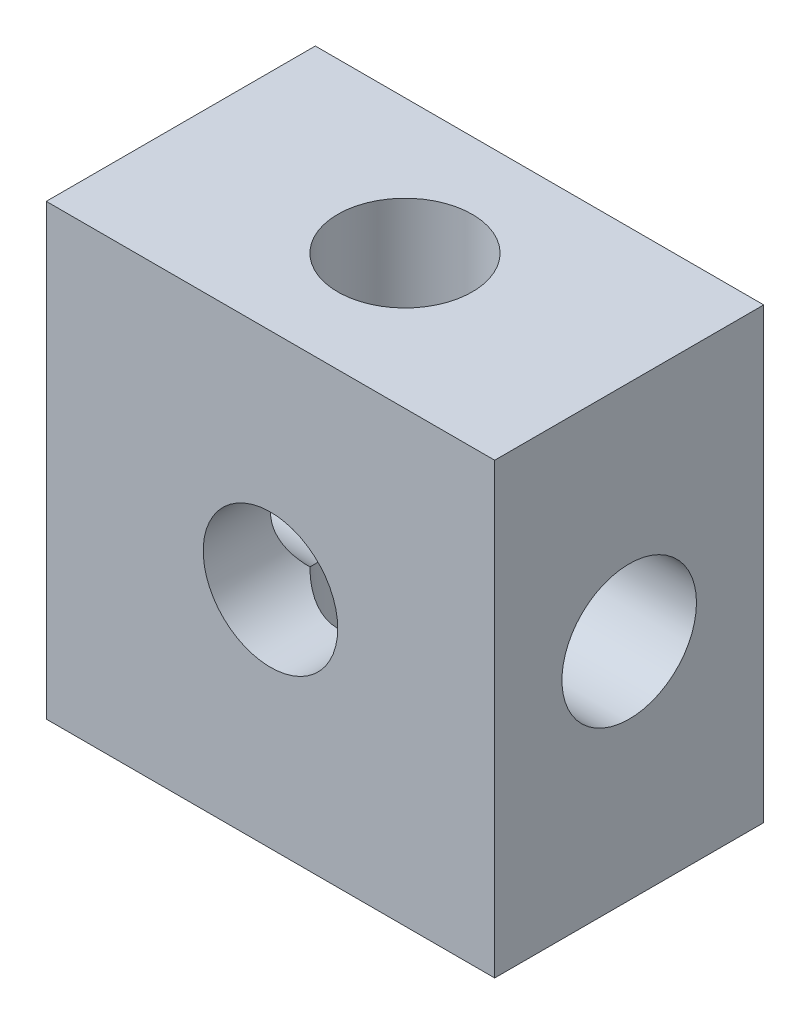
SolidWorks part; units mm, degrees
ref_plane "前视基准面" through (0, 0, 0) normal (0, 0, 1) x (1, 0, 0)
ref_plane "上视基准面" through (0, 0, 0) normal (0, 1, 0) x (1, 0, 0)
ref_plane "右视基准面" through (0, 0, 0) normal (1, 0, 0) x (0, 0, -1)
sketch "草图1" plane through (0, 0, 0) normal (0, 0, 1) x (1, 0, 0)
  line L1 (5, -5) -> (-5, -5)
  line L2 (5, -5) -> (5, 5)
  line L3 (5, 5) -> (-5, 5)
  line L4 (-5, -5) -> (-5, 5)
  line L5 (5, -5) -> (-5, 5) construction
  line L6 (5, 5) -> (-5, -5) construction
  point P0 (0, 0)
  dimension "D1" = 10
  dimension "D2" = 10
extrude "凸台-拉伸1" add sketch "草图1" along normal blind 6
sketch "草图2" plane through (0, 0, 6) normal (0, 0, 1) x (1, 0, 0)
  circle A0 centre (0, 0) radius 1.5
  dimension "D1" = 3
extrude "切除-拉伸1" cut sketch "草图2" against normal through all
sketch "草图3" plane through (0, 5, 0) normal (0, 1, 0) x (1, 0, 0)
  circle A0 centre (0, -3) radius 1.5
  dimension "D1" = 3
extrude "切除-拉伸2" cut sketch "草图3" against normal through all
sketch "草图4" plane through (5, 0, 0) normal (1, 0, 0) x (0, 0, -1)
  circle A0 centre (-3, 0) radius 1.5
extrude "切除-拉伸3" cut sketch "草图4" against normal through all
